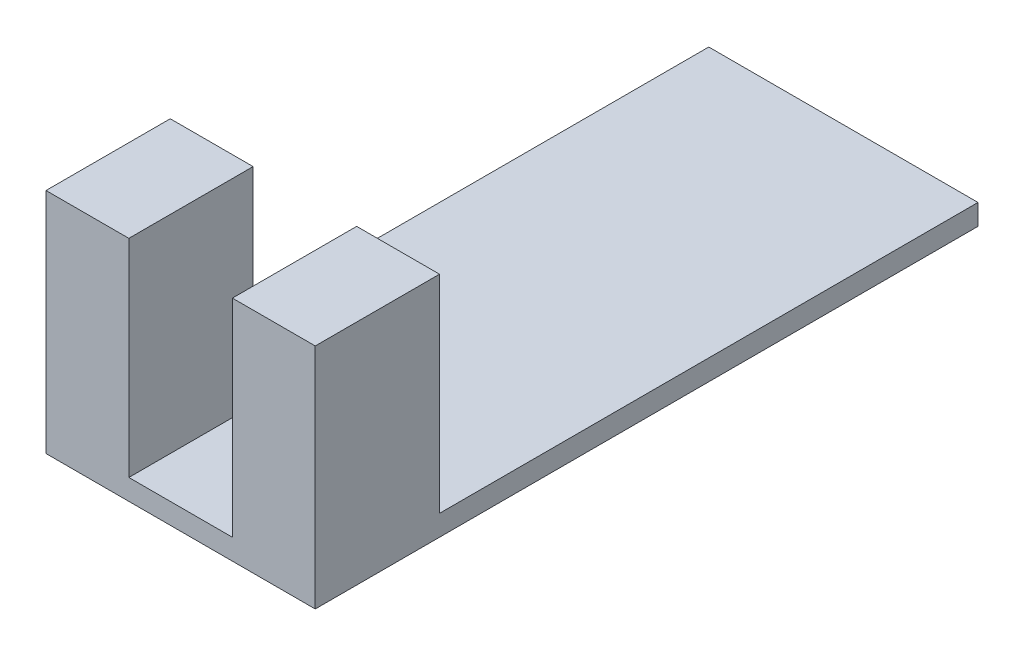
SolidWorks part; units mm, degrees
ref_plane "Front Plane" through (0, 0, 0) normal (0, 0, 1) x (1, 0, 0)
ref_plane "Top Plane" through (0, 0, 0) normal (0, 1, 0) x (1, 0, 0)
ref_plane "Right Plane" through (0, 0, 0) normal (1, 0, 0) x (0, 0, -1)
sketch "Sketch1" plane through (0, 0, 0) normal (0, 1, 0) x (1, 0, 0)
  line L1 (0, 0) -> (13, 0)
  line L2 (0, 0) -> (0, -32)
  line L3 (0, -32) -> (13, -32)
  line L4 (13, 0) -> (13, -32)
  dimension "D1" = 32
  dimension "D2" = 13
extrude "Boss-Extrude1" add sketch "Sketch1" along normal blind 1
sketch "Sketch2" plane through (0, 1, 0) normal (0, 1, 0) x (1, 0, 0)
  line L1 (13, -32) -> (9, -32)
  line L2 (13, -32) -> (13, -26)
  line L3 (13, -26) -> (9, -26)
  line L4 (9, -32) -> (9, -26)
  line L5 (0, -32) -> (4, -32)
  line L6 (0, -32) -> (0, -26)
  line L7 (0, -26) -> (4, -26)
  line L8 (4, -32) -> (4, -26)
  dimension "D1" = 6
  dimension "D2" = 4
  dimension "D3" = 4
extrude "Boss-Extrude2" add sketch "Sketch2" along normal blind 10
